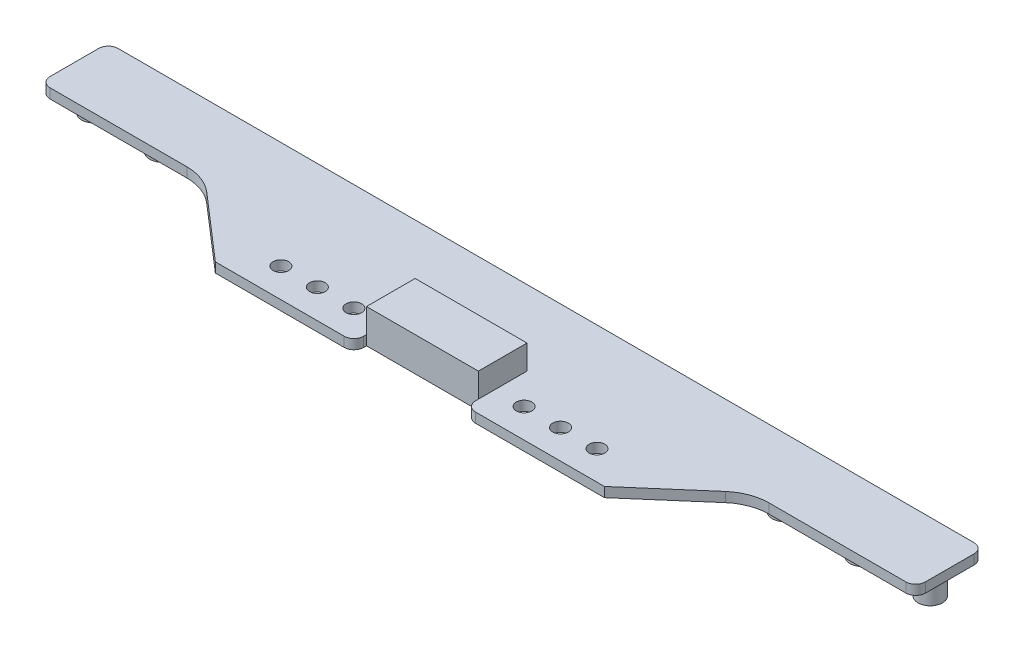
SolidWorks part; units mm, degrees
ref_plane "前视基准面" through (0, 0, 0) normal (0, 0, 1) x (1, 0, 0)
ref_plane "上视基准面" through (0, 0, 0) normal (0, 1, 0) x (1, 0, 0)
ref_plane "右视基准面" through (0, 0, 0) normal (1, 0, 0) x (0, 0, -1)
sketch "草图1" plane through (0, 0, 0) normal (0, 1, 0) x (1, 0, 0)
  line L0 (0, 0) -> (0, 35.723) construction
  line L1 (-11.5, 4.5011) -> (11.5, 4.5011)
  line L2 (11.5, 4.5011) -> (11.5, 1.9187)
  line L3 (11.5, 1.9187) -> (40, 1.9187)
  line L4 (40, 1.9187) -> (56.1464, 15.9187)
  line L5 (56.1464, 15.9187) -> (90, 15.9187)
  line L6 (90, 15.9187) -> (90, 29.9187)
  line L7 (90, 29.9187) -> (-90, 29.9187)
  line L8 (-90, 15.9187) -> (-90, 29.9187)
  line L9 (-56.1464, 15.9187) -> (-90, 15.9187)
  line L10 (-40, 1.9187) -> (-56.1464, 15.9187)
  line L11 (-11.5, 1.9187) -> (-40, 1.9187)
  line L12 (-11.5, 4.5011) -> (-11.5, 1.9187)
  circle A0 centre (17.5, 7.8964) radius 1.6
  circle A1 centre (25, 7.8964) radius 1.6
  circle A2 centre (32.5, 7.8964) radius 1.6
  circle A3 centre (-32.5, 7.8964) radius 1.6
  circle A4 centre (-25, 7.8964) radius 1.6
  circle A5 centre (-17.5, 7.8964) radius 1.6
  point P12 (0, 29.9187)
  point P17 (0, 4.5011)
  dimension "D4" = 3.2
  dimension "D1" = 35
  dimension "D2" = 50
  dimension "D3" = 65
  dimension "D5" = 28
  dimension "D6" = 180
  dimension "D7" = 14
  dimension "D8" = 23
  dimension "D9" = 80
extrude "凸台-拉伸1" add sketch "草图1" along normal blind 2
fillet "圆角1" radius 2 6 edges at (-90, 1, -15.9187) (-90, 1, -29.9187) (-11.5, 1, -1.9187) (11.5, 1, -1.9187) (90, 1, -15.9187) (90, 1, -29.9187)
fillet "圆角2" radius 10 2 edges at (56.1464, 1, -15.9187) (-56.1464, 1, -15.9187)
sketch "草图2" plane through (0, 0, 0) normal (0, -1, 0) x (1, 0, 0)
  line L0 (0, 0) -> (0, -51.1349) construction
  line L1 (88, -29.9187) -> (-88, -29.9187) construction
  circle A0 centre (-8, -22.9187) radius 2.5
  circle A1 centre (-24, -22.9187) radius 2.5
  circle A2 centre (-40, -22.9187) radius 2.5
  circle A3 centre (-56, -22.9187) radius 2.5
  circle A4 centre (-72, -22.9187) radius 2.5
  circle A5 centre (-86, -22.9187) radius 2.5
  circle A6 centre (8, -22.9187) radius 2.5
  circle A7 centre (24, -22.9187) radius 2.5
  circle A8 centre (40, -22.9187) radius 2.5
  circle A9 centre (56, -22.9187) radius 2.5
  circle A10 centre (72, -22.9187) radius 2.5
  circle A11 centre (86, -22.9187) radius 2.5
  dimension "D1" = 5
  dimension "D2" = 8
  dimension "D4" = 14
  dimension "D5" = 7
  dimension "D3" = 5
extrude "凸台-拉伸2" add sketch "草图2" along normal blind 5
sketch "草图3" plane through (0, 2, 0) normal (0, 1, 0) x (1, 0, 0)
  line L1 (-11.5, 14.5011) -> (11.5, 14.5011)
  line L2 (-11.5, 14.5011) -> (-11.5, 4.5011)
  line L3 (-11.5, 4.5011) -> (11.5, 4.5011)
  line L4 (11.5, 14.5011) -> (11.5, 4.5011)
  line L5 (-11.5, 14.5011) -> (11.5, 4.5011) construction
  line L6 (-11.5, 4.5011) -> (11.5, 14.5011) construction
  point P0 (0, 9.5011)
  dimension "D1" = 10
extrude "凸台-拉伸4" add sketch "草图3" along normal blind 5
